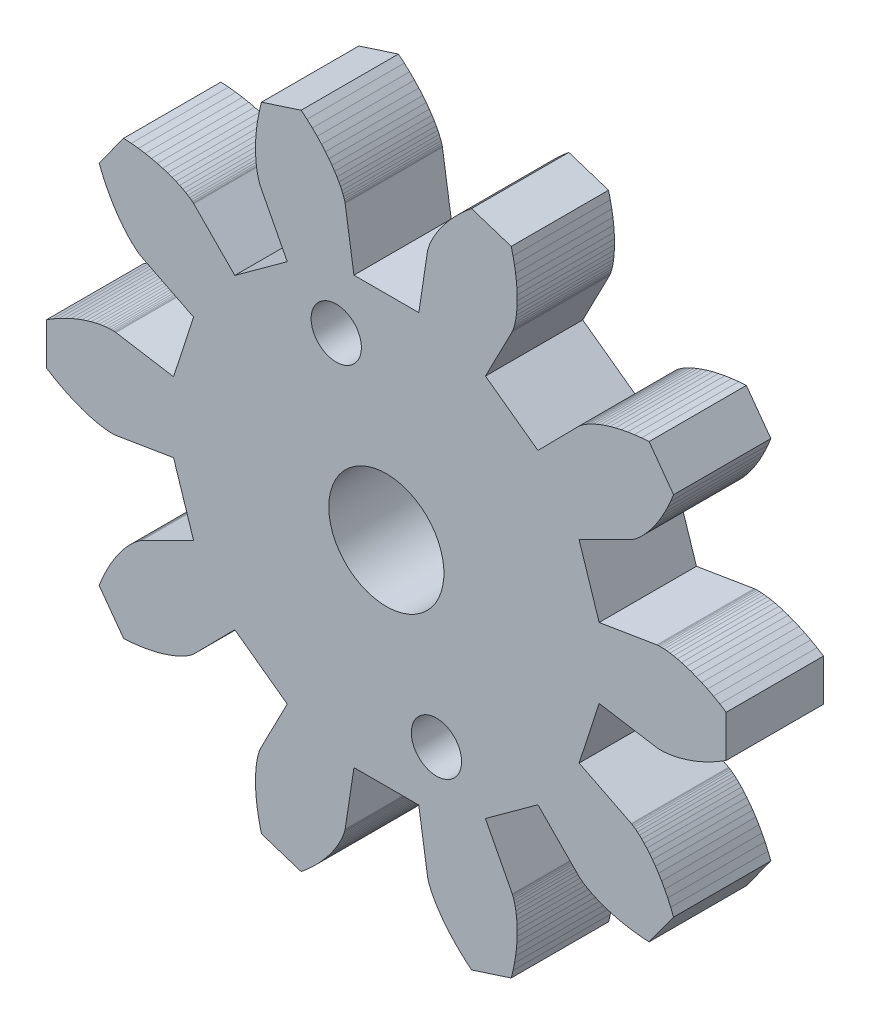
SolidWorks part; units mm, degrees
material "Acrylic (Medium-high impact)"
ref_plane "Front Plane" through (0, 0, 0) normal (0, 0, 1) x (1, 0, 0)
ref_plane "Top Plane" through (0, 0, 0) normal (0, 1, 0) x (1, 0, 0)
ref_plane "Right Plane" through (0, 0, 0) normal (1, 0, 0) x (0, 0, -1)
sketch "Model" plane through (0, 0, 0) normal (0, 0, 1) x (1, 0, 0)
  line L0 (13.1232, 2.1613) -> (16.679, 2.7469)
  line L1 (16.679, 2.7469) -> (16.6916, 2.7487)
  line L2 (16.6916, 2.7487) -> (16.7296, 2.7526)
  line L3 (16.7296, 2.7526) -> (16.793, 2.7567)
  line L4 (16.793, 2.7567) -> (16.8821, 2.7591)
  line L5 (16.8821, 2.7591) -> (16.9965, 2.7577)
  line L6 (16.9965, 2.7577) -> (17.1363, 2.7506)
  line L7 (17.1363, 2.7506) -> (17.301, 2.7358)
  line L8 (17.301, 2.7358) -> (17.4903, 2.7114)
  line L9 (17.4903, 2.7114) -> (17.7035, 2.6755)
  line L10 (17.7035, 2.6755) -> (17.9401, 2.6262)
  line L11 (17.9401, 2.6262) -> (18.1993, 2.5615)
  line L12 (18.1993, 2.5615) -> (18.4803, 2.4797)
  line L13 (18.4803, 2.4797) -> (18.7819, 2.3791)
  line L14 (18.7819, 2.3791) -> (19.1033, 2.2578)
  line L15 (19.1033, 2.2578) -> (19.4431, 2.1143)
  line L16 (19.4431, 2.1143) -> (19.8002, 1.947)
  line L17 (19.8002, 1.947) -> (20.1731, 1.7542)
  line L18 (20.1731, 1.7542) -> (20.5604, 1.5345)
  line L19 (20.5604, 1.5345) -> (20.9605, 1.2866)
  line L20 (20.9605, 1.2866) -> (20.9605, -1.2866)
  line L21 (20.9605, -1.2866) -> (20.5604, -1.5345)
  line L22 (20.5604, -1.5345) -> (20.1731, -1.7542)
  line L23 (20.1731, -1.7542) -> (19.8002, -1.947)
  line L24 (19.8002, -1.947) -> (19.4431, -2.1143)
  line L25 (19.4431, -2.1143) -> (19.1033, -2.2578)
  line L26 (19.1033, -2.2578) -> (18.7819, -2.3791)
  line L27 (18.7819, -2.3791) -> (18.4803, -2.4797)
  line L28 (18.4803, -2.4797) -> (18.1993, -2.5615)
  line L29 (18.1993, -2.5615) -> (17.9401, -2.6262)
  line L30 (17.9401, -2.6262) -> (17.7035, -2.6755)
  line L31 (17.7035, -2.6755) -> (17.4903, -2.7114)
  line L32 (17.4903, -2.7114) -> (17.301, -2.7358)
  line L33 (17.301, -2.7358) -> (17.1363, -2.7506)
  line L34 (17.1363, -2.7506) -> (16.9965, -2.7577)
  line L35 (16.9965, -2.7577) -> (16.8821, -2.7591)
  line L36 (16.8821, -2.7591) -> (16.793, -2.7567)
  line L37 (16.793, -2.7567) -> (16.7296, -2.7526)
  line L38 (16.7296, -2.7526) -> (16.6916, -2.7487)
  line L39 (16.6916, -2.7487) -> (16.679, -2.7469)
  line L40 (16.679, -2.7469) -> (13.1232, -2.1613)
  line L41 (13.1232, -2.1613) -> (11.8873, -5.9651)
  line L42 (11.8873, -5.9651) -> (15.1082, -7.5814)
  line L43 (15.1082, -7.5814) -> (15.1194, -7.5874)
  line L44 (15.1194, -7.5874) -> (15.1525, -7.6065)
  line L45 (15.1525, -7.6065) -> (15.2062, -7.6405)
  line L46 (15.2062, -7.6405) -> (15.2796, -7.6909)
  line L47 (15.2796, -7.6909) -> (15.3714, -7.7593)
  line L48 (15.3714, -7.7593) -> (15.4803, -7.8472)
  line L49 (15.4803, -7.8472) -> (15.6049, -7.9559)
  line L50 (15.6049, -7.9559) -> (15.7437, -8.0869)
  line L51 (15.7437, -8.0869) -> (15.8951, -8.2413)
  line L52 (15.8951, -8.2413) -> (16.0575, -8.4203)
  line L53 (16.0575, -8.4203) -> (16.2292, -8.625)
  line L54 (16.2292, -8.625) -> (16.4084, -8.8563)
  line L55 (16.4084, -8.8563) -> (16.5933, -9.115)
  line L56 (16.5933, -9.115) -> (16.782, -9.402)
  line L57 (16.782, -9.402) -> (16.9726, -9.7179)
  line L58 (16.9726, -9.7179) -> (17.1631, -10.0632)
  line L59 (17.1631, -10.0632) -> (17.3515, -10.4383)
  line L60 (17.3515, -10.4383) -> (17.5357, -10.8437)
  line L61 (17.5357, -10.8437) -> (17.7137, -11.2794)
  line L62 (17.7137, -11.2794) -> (16.2012, -13.3612)
  line L63 (16.2012, -13.3612) -> (15.7318, -13.3266)
  line L64 (15.7318, -13.3266) -> (15.2893, -13.2766)
  line L65 (15.2893, -13.2766) -> (14.8743, -13.2134)
  line L66 (14.8743, -13.2134) -> (14.4871, -13.1389)
  line L67 (14.4871, -13.1389) -> (14.1278, -13.0553)
  line L68 (14.1278, -13.0553) -> (13.7965, -12.9645)
  line L69 (13.7965, -12.9645) -> (13.4933, -12.8686)
  line L70 (13.4933, -12.8686) -> (13.218, -12.7696)
  line L71 (13.218, -12.7696) -> (12.9703, -12.6695)
  line L72 (12.9703, -12.6695) -> (12.7498, -12.5704)
  line L73 (12.7498, -12.5704) -> (12.5562, -12.4741)
  line L74 (12.5562, -12.4741) -> (12.3887, -12.3826)
  line L75 (12.3887, -12.3826) -> (12.2468, -12.2978)
  line L76 (12.2468, -12.2978) -> (12.1296, -12.2214)
  line L77 (12.1296, -12.2214) -> (12.0361, -12.1552)
  line L78 (12.0361, -12.1552) -> (11.9655, -12.1009)
  line L79 (11.9655, -12.1009) -> (11.9166, -12.0603)
  line L80 (11.9166, -12.0603) -> (11.8882, -12.0348)
  line L81 (11.8882, -12.0348) -> (11.879, -12.026)
  line L82 (11.879, -12.026) -> (9.3465, -9.4622)
  line L83 (9.3465, -9.4622) -> (6.1108, -11.813)
  line L84 (6.1108, -11.813) -> (7.7666, -15.0138)
  line L85 (7.7666, -15.0138) -> (7.7721, -15.0253)
  line L86 (7.7721, -15.0253) -> (7.7876, -15.0602)
  line L87 (7.7876, -15.0602) -> (7.8111, -15.1193)
  line L88 (7.8111, -15.1193) -> (7.8409, -15.2032)
  line L89 (7.8409, -15.2032) -> (7.875, -15.3125)
  line L90 (7.875, -15.3125) -> (7.9114, -15.4476)
  line L91 (7.9114, -15.4476) -> (7.9482, -15.6088)
  line L92 (7.9482, -15.6088) -> (7.9835, -15.7963)
  line L93 (7.9835, -15.7963) -> (8.0153, -16.0103)
  line L94 (8.0153, -16.0103) -> (8.0414, -16.2505)
  line L95 (8.0414, -16.2505) -> (8.06, -16.517)
  line L96 (8.06, -16.517) -> (8.0691, -16.8095)
  line L97 (8.0691, -16.8095) -> (8.0666, -17.1275)
  line L98 (8.0666, -17.1275) -> (8.0506, -17.4706)
  line L99 (8.0506, -17.4706) -> (8.0191, -17.8382)
  line L100 (8.0191, -17.8382) -> (7.9703, -18.2295)
  line L101 (7.9703, -18.2295) -> (7.9022, -18.6437)
  line L102 (7.9022, -18.6437) -> (7.8129, -19.0799)
  line L103 (7.8129, -19.0799) -> (7.7008, -19.5371)
  line L104 (7.7008, -19.5371) -> (5.2535, -20.3322)
  line L105 (5.2535, -20.3322) -> (4.8941, -20.0283)
  line L106 (4.8941, -20.0283) -> (4.5655, -19.7279)
  line L107 (4.5655, -19.7279) -> (4.2669, -19.4328)
  line L108 (4.2669, -19.4328) -> (3.9974, -19.1449)
  line L109 (3.9974, -19.1449) -> (3.7559, -18.866)
  line L110 (3.7559, -18.866) -> (3.5413, -18.5979)
  line L111 (3.5413, -18.5979) -> (3.3523, -18.342)
  line L112 (3.3523, -18.342) -> (3.1878, -18.1001)
  line L113 (3.1878, -18.1001) -> (3.0462, -17.8736)
  line L114 (3.0462, -17.8736) -> (2.9261, -17.6638)
  line L115 (2.9261, -17.6638) -> (2.826, -17.4721)
  line L116 (2.826, -17.4721) -> (2.7444, -17.2997)
  line L117 (2.7444, -17.2997) -> (2.6794, -17.1476)
  line L118 (2.6794, -17.1476) -> (2.6295, -17.0169)
  line L119 (2.6295, -17.0169) -> (2.5928, -16.9084)
  line L120 (2.5928, -16.9084) -> (2.5675, -16.823)
  line L121 (2.5675, -16.823) -> (2.5518, -16.7614)
  line L122 (2.5518, -16.7614) -> (2.5438, -16.7241)
  line L123 (2.5438, -16.7241) -> (2.5416, -16.7115)
  line L124 (2.5416, -16.7115) -> (1.9998, -13.1488)
  line L125 (1.9998, -13.1488) -> (-1.9998, -13.1488)
  line L126 (-1.9998, -13.1488) -> (-2.5416, -16.7115)
  line L127 (-2.5416, -16.7115) -> (-2.5438, -16.7241)
  line L128 (-2.5438, -16.7241) -> (-2.5518, -16.7614)
  line L129 (-2.5518, -16.7614) -> (-2.5675, -16.823)
  line L130 (-2.5675, -16.823) -> (-2.5928, -16.9084)
  line L131 (-2.5928, -16.9084) -> (-2.6295, -17.0169)
  line L132 (-2.6295, -17.0169) -> (-2.6794, -17.1476)
  line L133 (-2.6794, -17.1476) -> (-2.7444, -17.2997)
  line L134 (-2.7444, -17.2997) -> (-2.826, -17.4721)
  line L135 (-2.826, -17.4721) -> (-2.9261, -17.6638)
  line L136 (-2.9261, -17.6638) -> (-3.0462, -17.8736)
  line L137 (-3.0462, -17.8736) -> (-3.1878, -18.1001)
  line L138 (-3.1878, -18.1001) -> (-3.3523, -18.342)
  line L139 (-3.3523, -18.342) -> (-3.5413, -18.5979)
  line L140 (-3.5413, -18.5979) -> (-3.7559, -18.866)
  line L141 (-3.7559, -18.866) -> (-3.9974, -19.1449)
  line L142 (-3.9974, -19.1449) -> (-4.2669, -19.4328)
  line L143 (-4.2669, -19.4328) -> (-4.5655, -19.7279)
  line L144 (-4.5655, -19.7279) -> (-4.8941, -20.0283)
  line L145 (-4.8941, -20.0283) -> (-5.2535, -20.3322)
  line L146 (-5.2535, -20.3322) -> (-7.7008, -19.5371)
  line L147 (-7.7008, -19.5371) -> (-7.8129, -19.0799)
  line L148 (-7.8129, -19.0799) -> (-7.9022, -18.6437)
  line L149 (-7.9022, -18.6437) -> (-7.9703, -18.2295)
  line L150 (-7.9703, -18.2295) -> (-8.0191, -17.8382)
  line L151 (-8.0191, -17.8382) -> (-8.0506, -17.4706)
  line L152 (-8.0506, -17.4706) -> (-8.0666, -17.1275)
  line L153 (-8.0666, -17.1275) -> (-8.0691, -16.8095)
  line L154 (-8.0691, -16.8095) -> (-8.06, -16.517)
  line L155 (-8.06, -16.517) -> (-8.0414, -16.2505)
  line L156 (-8.0414, -16.2505) -> (-8.0153, -16.0103)
  line L157 (-8.0153, -16.0103) -> (-7.9835, -15.7963)
  line L158 (-7.9835, -15.7963) -> (-7.9482, -15.6088)
  line L159 (-7.9482, -15.6088) -> (-7.9114, -15.4476)
  line L160 (-7.9114, -15.4476) -> (-7.875, -15.3125)
  line L161 (-7.875, -15.3125) -> (-7.8409, -15.2032)
  line L162 (-7.8409, -15.2032) -> (-7.8111, -15.1193)
  line L163 (-7.8111, -15.1193) -> (-7.7876, -15.0602)
  line L164 (-7.7876, -15.0602) -> (-7.7721, -15.0253)
  line L165 (-7.7721, -15.0253) -> (-7.7666, -15.0138)
  line L166 (-7.7666, -15.0138) -> (-6.1108, -11.813)
  line L167 (-6.1108, -11.813) -> (-9.3465, -9.4622)
  line L168 (-9.3465, -9.4622) -> (-11.879, -12.026)
  line L169 (-11.879, -12.026) -> (-11.8882, -12.0348)
  line L170 (-11.8882, -12.0348) -> (-11.9166, -12.0603)
  line L171 (-11.9166, -12.0603) -> (-11.9655, -12.1009)
  line L172 (-11.9655, -12.1009) -> (-12.0361, -12.1552)
  line L173 (-12.0361, -12.1552) -> (-12.1296, -12.2214)
  line L174 (-12.1296, -12.2214) -> (-12.2468, -12.2978)
  line L175 (-12.2468, -12.2978) -> (-12.3887, -12.3826)
  line L176 (-12.3887, -12.3826) -> (-12.5562, -12.4741)
  line L177 (-12.5562, -12.4741) -> (-12.7498, -12.5704)
  line L178 (-12.7498, -12.5704) -> (-12.9703, -12.6695)
  line L179 (-12.9703, -12.6695) -> (-13.218, -12.7696)
  line L180 (-13.218, -12.7696) -> (-13.4933, -12.8686)
  line L181 (-13.4933, -12.8686) -> (-13.7965, -12.9645)
  line L182 (-13.7965, -12.9645) -> (-14.1278, -13.0553)
  line L183 (-14.1278, -13.0553) -> (-14.4871, -13.1389)
  line L184 (-14.4871, -13.1389) -> (-14.8743, -13.2134)
  line L185 (-14.8743, -13.2134) -> (-15.2893, -13.2766)
  line L186 (-15.2893, -13.2766) -> (-15.7318, -13.3266)
  line L187 (-15.7318, -13.3266) -> (-16.2012, -13.3612)
  line L188 (-16.2012, -13.3612) -> (-17.7137, -11.2794)
  line L189 (-17.7137, -11.2794) -> (-17.5357, -10.8437)
  line L190 (-17.5357, -10.8437) -> (-17.3515, -10.4383)
  line L191 (-17.3515, -10.4383) -> (-17.1631, -10.0632)
  line L192 (-17.1631, -10.0632) -> (-16.9726, -9.7179)
  line L193 (-16.9726, -9.7179) -> (-16.782, -9.402)
  line L194 (-16.782, -9.402) -> (-16.5933, -9.115)
  line L195 (-16.5933, -9.115) -> (-16.4084, -8.8563)
  line L196 (-16.4084, -8.8563) -> (-16.2292, -8.625)
  line L197 (-16.2292, -8.625) -> (-16.0575, -8.4203)
  line L198 (-16.0575, -8.4203) -> (-15.8951, -8.2413)
  line L199 (-15.8951, -8.2413) -> (-15.7437, -8.0869)
  line L200 (-15.7437, -8.0869) -> (-15.6049, -7.9559)
  line L201 (-15.6049, -7.9559) -> (-15.4803, -7.8472)
  line L202 (-15.4803, -7.8472) -> (-15.3714, -7.7593)
  line L203 (-15.3714, -7.7593) -> (-15.2796, -7.6909)
  line L204 (-15.2796, -7.6909) -> (-15.2062, -7.6405)
  line L205 (-15.2062, -7.6405) -> (-15.1525, -7.6065)
  line L206 (-15.1525, -7.6065) -> (-15.1194, -7.5874)
  line L207 (-15.1194, -7.5874) -> (-15.1082, -7.5814)
  line L208 (-15.1082, -7.5814) -> (-11.8873, -5.9651)
  line L209 (-11.8873, -5.9651) -> (-13.1232, -2.1613)
  line L210 (-13.1232, -2.1613) -> (-16.679, -2.7469)
  line L211 (-16.679, -2.7469) -> (-16.6916, -2.7487)
  line L212 (-16.6916, -2.7487) -> (-16.7296, -2.7526)
  line L213 (-16.7296, -2.7526) -> (-16.793, -2.7567)
  line L214 (-16.793, -2.7567) -> (-16.8821, -2.7591)
  line L215 (-16.8821, -2.7591) -> (-16.9965, -2.7577)
  line L216 (-16.9965, -2.7577) -> (-17.1363, -2.7506)
  line L217 (-17.1363, -2.7506) -> (-17.301, -2.7358)
  line L218 (-17.301, -2.7358) -> (-17.4903, -2.7114)
  line L219 (-17.4903, -2.7114) -> (-17.7035, -2.6755)
  line L220 (-17.7035, -2.6755) -> (-17.9401, -2.6262)
  line L221 (-17.9401, -2.6262) -> (-18.1993, -2.5615)
  line L222 (-18.1993, -2.5615) -> (-18.4803, -2.4797)
  line L223 (-18.4803, -2.4797) -> (-18.7819, -2.3791)
  line L224 (-18.7819, -2.3791) -> (-19.1033, -2.2578)
  line L225 (-19.1033, -2.2578) -> (-19.4431, -2.1143)
  line L226 (-19.4431, -2.1143) -> (-19.8002, -1.947)
  line L227 (-19.8002, -1.947) -> (-20.1731, -1.7542)
  line L228 (-20.1731, -1.7542) -> (-20.5604, -1.5345)
  line L229 (-20.5604, -1.5345) -> (-20.9605, -1.2866)
  line L230 (-20.9605, -1.2866) -> (-20.9605, 1.2866)
  line L231 (-20.9605, 1.2866) -> (-20.5604, 1.5345)
  line L232 (-20.5604, 1.5345) -> (-20.1731, 1.7542)
  line L233 (-20.1731, 1.7542) -> (-19.8002, 1.947)
  line L234 (-19.8002, 1.947) -> (-19.4431, 2.1143)
  line L235 (-19.4431, 2.1143) -> (-19.1033, 2.2578)
  line L236 (-19.1033, 2.2578) -> (-18.7819, 2.3791)
  line L237 (-18.7819, 2.3791) -> (-18.4803, 2.4797)
  line L238 (-18.4803, 2.4797) -> (-18.1993, 2.5615)
  line L239 (-18.1993, 2.5615) -> (-17.9401, 2.6262)
  line L240 (-17.9401, 2.6262) -> (-17.7035, 2.6755)
  line L241 (-17.7035, 2.6755) -> (-17.4903, 2.7114)
  line L242 (-17.4903, 2.7114) -> (-17.301, 2.7358)
  line L243 (-17.301, 2.7358) -> (-17.1363, 2.7506)
  line L244 (-17.1363, 2.7506) -> (-16.9965, 2.7577)
  line L245 (-16.9965, 2.7577) -> (-16.8821, 2.7591)
  line L246 (-16.8821, 2.7591) -> (-16.793, 2.7567)
  line L247 (-16.793, 2.7567) -> (-16.7296, 2.7526)
  line L248 (-16.7296, 2.7526) -> (-16.6916, 2.7487)
  line L249 (-16.6916, 2.7487) -> (-16.679, 2.7469)
  line L250 (-16.679, 2.7469) -> (-13.1232, 2.1613)
  line L251 (-13.1232, 2.1613) -> (-11.8873, 5.9651)
  line L252 (-11.8873, 5.9651) -> (-15.1082, 7.5814)
  line L253 (-15.1082, 7.5814) -> (-15.1194, 7.5874)
  line L254 (-15.1194, 7.5874) -> (-15.1525, 7.6065)
  line L255 (-15.1525, 7.6065) -> (-15.2062, 7.6405)
  line L256 (-15.2062, 7.6405) -> (-15.2796, 7.6909)
  line L257 (-15.2796, 7.6909) -> (-15.3714, 7.7593)
  line L258 (-15.3714, 7.7593) -> (-15.4803, 7.8472)
  line L259 (-15.4803, 7.8472) -> (-15.6049, 7.9559)
  line L260 (-15.6049, 7.9559) -> (-15.7437, 8.0869)
  line L261 (-15.7437, 8.0869) -> (-15.8951, 8.2413)
  line L262 (-15.8951, 8.2413) -> (-16.0575, 8.4203)
  line L263 (-16.0575, 8.4203) -> (-16.2292, 8.625)
  line L264 (-16.2292, 8.625) -> (-16.4084, 8.8563)
  line L265 (-16.4084, 8.8563) -> (-16.5933, 9.115)
  line L266 (-16.5933, 9.115) -> (-16.782, 9.402)
  line L267 (-16.782, 9.402) -> (-16.9726, 9.7179)
  line L268 (-16.9726, 9.7179) -> (-17.1631, 10.0632)
  line L269 (-17.1631, 10.0632) -> (-17.3515, 10.4383)
  line L270 (-17.3515, 10.4383) -> (-17.5357, 10.8437)
  line L271 (-17.5357, 10.8437) -> (-17.7137, 11.2794)
  line L272 (-17.7137, 11.2794) -> (-16.2012, 13.3612)
  line L273 (-16.2012, 13.3612) -> (-15.7318, 13.3266)
  line L274 (-15.7318, 13.3266) -> (-15.2893, 13.2766)
  line L275 (-15.2893, 13.2766) -> (-14.8743, 13.2134)
  line L276 (-14.8743, 13.2134) -> (-14.4871, 13.1389)
  line L277 (-14.4871, 13.1389) -> (-14.1278, 13.0553)
  line L278 (-14.1278, 13.0553) -> (-13.7965, 12.9645)
  line L279 (-13.7965, 12.9645) -> (-13.4933, 12.8686)
  line L280 (-13.4933, 12.8686) -> (-13.218, 12.7696)
  line L281 (-13.218, 12.7696) -> (-12.9703, 12.6695)
  line L282 (-12.9703, 12.6695) -> (-12.7498, 12.5704)
  line L283 (-12.7498, 12.5704) -> (-12.5562, 12.4741)
  line L284 (-12.5562, 12.4741) -> (-12.3887, 12.3826)
  line L285 (-12.3887, 12.3826) -> (-12.2468, 12.2978)
  line L286 (-12.2468, 12.2978) -> (-12.1296, 12.2214)
  line L287 (-12.1296, 12.2214) -> (-12.0361, 12.1552)
  line L288 (-12.0361, 12.1552) -> (-11.9655, 12.1009)
  line L289 (-11.9655, 12.1009) -> (-11.9166, 12.0603)
  line L290 (-11.9166, 12.0603) -> (-11.8882, 12.0348)
  line L291 (-11.8882, 12.0348) -> (-11.879, 12.026)
  line L292 (-11.879, 12.026) -> (-9.3465, 9.4622)
  line L293 (-9.3465, 9.4622) -> (-6.1108, 11.813)
  line L294 (-6.1108, 11.813) -> (-7.7666, 15.0138)
  line L295 (-7.7666, 15.0138) -> (-7.7721, 15.0253)
  line L296 (-7.7721, 15.0253) -> (-7.7876, 15.0602)
  line L297 (-7.7876, 15.0602) -> (-7.8111, 15.1193)
  line L298 (-7.8111, 15.1193) -> (-7.8409, 15.2032)
  line L299 (-7.8409, 15.2032) -> (-7.875, 15.3125)
  line L300 (-7.875, 15.3125) -> (-7.9114, 15.4476)
  line L301 (-7.9114, 15.4476) -> (-7.9482, 15.6088)
  line L302 (-7.9482, 15.6088) -> (-7.9835, 15.7963)
  line L303 (-7.9835, 15.7963) -> (-8.0153, 16.0103)
  line L304 (-8.0153, 16.0103) -> (-8.0414, 16.2505)
  line L305 (-8.0414, 16.2505) -> (-8.06, 16.517)
  line L306 (-8.06, 16.517) -> (-8.0691, 16.8095)
  line L307 (-8.0691, 16.8095) -> (-8.0666, 17.1275)
  line L308 (-8.0666, 17.1275) -> (-8.0506, 17.4706)
  line L309 (-8.0506, 17.4706) -> (-8.0191, 17.8382)
  line L310 (-8.0191, 17.8382) -> (-7.9703, 18.2295)
  line L311 (-7.9703, 18.2295) -> (-7.9022, 18.6437)
  line L312 (-7.9022, 18.6437) -> (-7.8129, 19.0799)
  line L313 (-7.8129, 19.0799) -> (-7.7008, 19.5371)
  line L314 (-7.7008, 19.5371) -> (-5.2535, 20.3322)
  line L315 (-5.2535, 20.3322) -> (-4.8941, 20.0283)
  line L316 (-4.8941, 20.0283) -> (-4.5655, 19.7279)
  line L317 (-4.5655, 19.7279) -> (-4.2669, 19.4328)
  line L318 (-4.2669, 19.4328) -> (-3.9974, 19.1449)
  line L319 (-3.9974, 19.1449) -> (-3.7559, 18.866)
  line L320 (-3.7559, 18.866) -> (-3.5413, 18.5979)
  line L321 (-3.5413, 18.5979) -> (-3.3523, 18.342)
  line L322 (-3.3523, 18.342) -> (-3.1878, 18.1001)
  line L323 (-3.1878, 18.1001) -> (-3.0462, 17.8736)
  line L324 (-3.0462, 17.8736) -> (-2.9261, 17.6638)
  line L325 (-2.9261, 17.6638) -> (-2.826, 17.4721)
  line L326 (-2.826, 17.4721) -> (-2.7444, 17.2997)
  line L327 (-2.7444, 17.2997) -> (-2.6794, 17.1476)
  line L328 (-2.6794, 17.1476) -> (-2.6295, 17.0169)
  line L329 (-2.6295, 17.0169) -> (-2.5928, 16.9084)
  line L330 (-2.5928, 16.9084) -> (-2.5675, 16.823)
  line L331 (-2.5675, 16.823) -> (-2.5518, 16.7614)
  line L332 (-2.5518, 16.7614) -> (-2.5438, 16.7241)
  line L333 (-2.5438, 16.7241) -> (-2.5416, 16.7115)
  line L334 (-2.5416, 16.7115) -> (-1.9998, 13.1488)
  line L335 (-1.9998, 13.1488) -> (1.9998, 13.1488)
  line L336 (1.9998, 13.1488) -> (2.5416, 16.7115)
  line L337 (2.5416, 16.7115) -> (2.5438, 16.7241)
  line L338 (2.5438, 16.7241) -> (2.5518, 16.7614)
  line L339 (2.5518, 16.7614) -> (2.5675, 16.823)
  line L340 (2.5675, 16.823) -> (2.5928, 16.9084)
  line L341 (2.5928, 16.9084) -> (2.6295, 17.0169)
  line L342 (2.6295, 17.0169) -> (2.6794, 17.1476)
  line L343 (2.6794, 17.1476) -> (2.7444, 17.2997)
  line L344 (2.7444, 17.2997) -> (2.826, 17.4721)
  line L345 (2.826, 17.4721) -> (2.9261, 17.6638)
  line L346 (2.9261, 17.6638) -> (3.0462, 17.8736)
  line L347 (3.0462, 17.8736) -> (3.1878, 18.1001)
  line L348 (3.1878, 18.1001) -> (3.3523, 18.342)
  line L349 (3.3523, 18.342) -> (3.5413, 18.5979)
  line L350 (3.5413, 18.5979) -> (3.7559, 18.866)
  line L351 (3.7559, 18.866) -> (3.9974, 19.1449)
  line L352 (3.9974, 19.1449) -> (4.2669, 19.4328)
  line L353 (4.2669, 19.4328) -> (4.5655, 19.7279)
  line L354 (4.5655, 19.7279) -> (4.8941, 20.0283)
  line L355 (4.8941, 20.0283) -> (5.2535, 20.3322)
  line L356 (5.2535, 20.3322) -> (7.7008, 19.5371)
  line L357 (7.7008, 19.5371) -> (7.8129, 19.0799)
  line L358 (7.8129, 19.0799) -> (7.9022, 18.6437)
  line L359 (7.9022, 18.6437) -> (7.9703, 18.2295)
  line L360 (7.9703, 18.2295) -> (8.0191, 17.8382)
  line L361 (8.0191, 17.8382) -> (8.0506, 17.4706)
  line L362 (8.0506, 17.4706) -> (8.0666, 17.1275)
  line L363 (8.0666, 17.1275) -> (8.0691, 16.8095)
  line L364 (8.0691, 16.8095) -> (8.06, 16.517)
  line L365 (8.06, 16.517) -> (8.0414, 16.2505)
  line L366 (8.0414, 16.2505) -> (8.0153, 16.0103)
  line L367 (8.0153, 16.0103) -> (7.9835, 15.7963)
  line L368 (7.9835, 15.7963) -> (7.9482, 15.6088)
  line L369 (7.9482, 15.6088) -> (7.9114, 15.4476)
  line L370 (7.9114, 15.4476) -> (7.875, 15.3125)
  line L371 (7.875, 15.3125) -> (7.8409, 15.2032)
  line L372 (7.8409, 15.2032) -> (7.8111, 15.1193)
  line L373 (7.8111, 15.1193) -> (7.7876, 15.0602)
  line L374 (7.7876, 15.0602) -> (7.7721, 15.0253)
  line L375 (7.7721, 15.0253) -> (7.7666, 15.0138)
  line L376 (7.7666, 15.0138) -> (6.1108, 11.813)
  line L377 (6.1108, 11.813) -> (9.3465, 9.4622)
  line L378 (9.3465, 9.4622) -> (11.879, 12.026)
  line L379 (11.879, 12.026) -> (11.8882, 12.0348)
  line L380 (11.8882, 12.0348) -> (11.9166, 12.0603)
  line L381 (11.9166, 12.0603) -> (11.9655, 12.1009)
  line L382 (11.9655, 12.1009) -> (12.0361, 12.1552)
  line L383 (12.0361, 12.1552) -> (12.1296, 12.2214)
  line L384 (12.1296, 12.2214) -> (12.2468, 12.2978)
  line L385 (12.2468, 12.2978) -> (12.3887, 12.3826)
  line L386 (12.3887, 12.3826) -> (12.5562, 12.4741)
  line L387 (12.5562, 12.4741) -> (12.7498, 12.5704)
  line L388 (12.7498, 12.5704) -> (12.9703, 12.6695)
  line L389 (12.9703, 12.6695) -> (13.218, 12.7696)
  line L390 (13.218, 12.7696) -> (13.4933, 12.8686)
  line L391 (13.4933, 12.8686) -> (13.7965, 12.9645)
  line L392 (13.7965, 12.9645) -> (14.1278, 13.0553)
  line L393 (14.1278, 13.0553) -> (14.4871, 13.1389)
  line L394 (14.4871, 13.1389) -> (14.8743, 13.2134)
  line L395 (14.8743, 13.2134) -> (15.2893, 13.2766)
  line L396 (15.2893, 13.2766) -> (15.7318, 13.3266)
  line L397 (15.7318, 13.3266) -> (16.2012, 13.3612)
  line L398 (16.2012, 13.3612) -> (17.7137, 11.2794)
  line L399 (17.7137, 11.2794) -> (17.5357, 10.8437)
  line L400 (17.5357, 10.8437) -> (17.3515, 10.4383)
  line L401 (17.3515, 10.4383) -> (17.1631, 10.0632)
  line L402 (17.1631, 10.0632) -> (16.9726, 9.7179)
  line L403 (16.9726, 9.7179) -> (16.782, 9.402)
  line L404 (16.782, 9.402) -> (16.5933, 9.115)
  line L405 (16.5933, 9.115) -> (16.4084, 8.8563)
  line L406 (16.4084, 8.8563) -> (16.2292, 8.625)
  line L407 (16.2292, 8.625) -> (16.0575, 8.4203)
  line L408 (16.0575, 8.4203) -> (15.8951, 8.2413)
  line L409 (15.8951, 8.2413) -> (15.7437, 8.0869)
  line L410 (15.7437, 8.0869) -> (15.6049, 7.9559)
  line L411 (15.6049, 7.9559) -> (15.4803, 7.8472)
  line L412 (15.4803, 7.8472) -> (15.3714, 7.7593)
  line L413 (15.3714, 7.7593) -> (15.2796, 7.6909)
  line L414 (15.2796, 7.6909) -> (15.2062, 7.6405)
  line L415 (15.2062, 7.6405) -> (15.1525, 7.6065)
  line L416 (15.1525, 7.6065) -> (15.1194, 7.5874)
  line L417 (15.1194, 7.5874) -> (15.1082, 7.5814)
  line L418 (15.1082, 7.5814) -> (11.8873, 5.9651)
  line L419 (11.8873, 5.9651) -> (13.1232, 2.1613)
extrude "Boss-Extrude1" add sketch "Model" along normal blind 6 contours L210 L211 L212 L213 L214 L215 L216 L217 L218 L219 L220 L221 L222 L223 L224 L225 L226 L227 L228 L229 L230 L231 L232 L233 L234 L235 L236 L237 L238 L239 L240 L241 L242 L243 L244 L245 L246 L247 L248 L249 L250 L251 L252 L253 L254 L255 L256 L257 L258 L259 L260 L261 L262 L263 L264 L265 L266 L267 L268 L269 L270 L271 L272 L273 L274 L275 L276 L277 L278 L279 L280 L281 L282 L283 L284 L285 L286 L287 L288 L289 L290 L291 L292 L293 L294 L295 L296 L297 L298 L299 L300 L301 L302 L303 L304 L305 L306 L307 L308 L309 L310 L311 L312 L313 L314 L315 L316 L317 L318 L319 L320 L321 L322 L323 L324 L325 L326 L327 L328 L329 L330 L331 L332 L333 L334 L335 L336 L337 L338 L339 L340 L341 L342 L343 L344 L345 L346 L347 L348 L349 L350 L351 L352 L353 L354 L355 L356 L357 L358 L359 L360 L361 L362 L363 L364 L365 L366 L367 L368 L369 L370 L371 L372 L373 L374 L375 L376 L377 L378 L379 L380 L381 L382 L383 L384 L385 L386 L387 L388 L389 L390 L391 L392 L393 L394 L395 L396 L397 L398 L399 L400 L401 L402 L403 L404 L405 L406 L407 L408 L409 L410 L411 L412 L413 L414 L415 L416 L417 L418 L419 L0 L1 L2 L3 L4 L5 L6 L7 L8 L9 L10 L11 L12 L13 L14 L15 L16 L17 L18 L19 L20 L21 L22 L23 L24 L25 L26 L27 L28 L29 L30 L31 L32 L33 L34 L35 L36 L37 L38 L39 L40 L41 L42 L43 L44 L45 L46 L47 L48 L49 L50 L51 L52 L53 L54 L55 L56 L57 L58 L59 L60 L61 L62 L63 L64 L65 L66 L67 L68 L69 L70 L71 L72 L73 L74 L75 L76 L77 L78 L79 L80 L81 L82 L83 L84 L85 L86 L87 L88 L89 L90 L91 L92 L93 L94 L95 L96 L97 L98 L99 L100 L101 L102 L103 L104 L105 L106 L107 L108 L109 L110 L111 L112 L113 L114 L115 L116 L117 L118 L119 L120 L121 L122 L123 L124 L125 L126 L127 L128 L129 L130 L131 L132 L133 L134 L135 L136 L137 L138 L139 L140 L141 L142 L143 L144 L145 L146 L147 L148 L149 L150 L151 L152 L153 L154 L155 L156 L157 L158 L159 L160 L161 L162 L163 L164 L165 L166 L167 L168 L169 L170 L171 L172 L173 L174 L175 L176 L177 L178 L179 L180 L181 L182 L183 L184 L185 L186 L187 L188 L189 L190 L191 L192 L193 L194 L195 L196 L197 L198 L199 L200 L201 L202 L203 L204 L205 L206 L207 L208 L209
sketch "Sketch3" plane through (0, 0, 6) normal (0, 0, 1) x (1, 0, 0)
  line L0 (-6.1108, 11.813) -> (-1.9998, 13.1488) construction
  line L1 (-4.0553, 12.4809) -> (0, 0) construction
  circle A0 centre (-3.0902, 9.5106) radius 1.55
  dimension "D1" = 3.1
  dimension "D2" = 10
extrude "Cut-Extrude2" cut sketch "Sketch3" against normal through all
sketch "Sketch4" plane through (0, 0, 6) normal (0, 0, 1) x (1, 0, 0)
  circle A0 centre (0, 0) radius 17.5 construction
  dimension "D1" = 35
sketch "Sketch8" plane through (0, 0, 0) normal (0, 0, -1) x (-1, 0, 0)
  circle A0 centre (0, 0) radius 3.55
  dimension "D1" = 7.1
extrude "Cut-Extrude4" cut sketch "Sketch8" against normal through all
pattern_circular "CirPattern1" count 2 over 360 about axis through (0, 0, 0) along (0, 0, 1) of "Cut-Extrude2"
